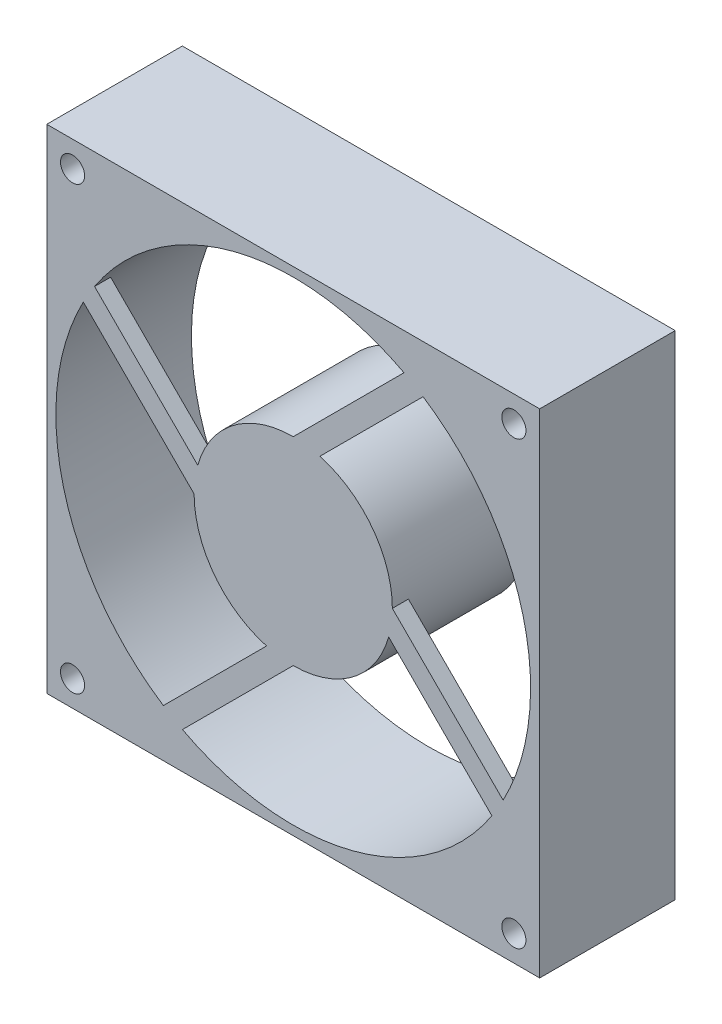
SolidWorks part; units mm, degrees
ref_plane "Front Plane" through (0, 0, 0) normal (0, 0, 1) x (1, 0, 0)
ref_plane "Top Plane" through (0, 0, 0) normal (0, 1, 0) x (1, 0, 0)
ref_plane "Right Plane" through (0, 0, 0) normal (1, 0, 0) x (0, 0, -1)
sketch "Sketch1" plane through (0, 0, 0) normal (0, 0, 1) x (1, 0, 0)
  line L1 (-46, -46) -> (46, -46)
  line L2 (-46, -46) -> (-46, 46)
  line L3 (-46, 46) -> (46, 46)
  line L4 (46, -46) -> (46, 46)
  line L5 (-46, -46) -> (46, 46) construction
  line L6 (-46, 46) -> (46, -46) construction
  line L7 (-41.189, -41.189) -> (41.189, -41.189) construction
  line L8 (-41.189, -41.189) -> (-41.189, 41.189) construction
  line L9 (-41.189, 41.189) -> (41.189, 41.189) construction
  line L10 (41.189, -41.189) -> (41.189, 41.189) construction
  line L11 (-41.189, -41.189) -> (41.189, 41.189) construction
  line L12 (-41.189, 41.189) -> (41.189, -41.189) construction
  circle A0 centre (-41.189, 41.189) radius 2.25
  circle A1 centre (41.189, 41.189) radius 2.25
  circle A2 centre (41.189, -41.189) radius 2.25
  circle A3 centre (-41.189, -41.189) radius 2.25
  circle A4 centre (0, 0) radius 44.3
  circle A5 centre (0, 0) radius 18.5
  point P0 (0, 0)
  point P6 (0, 0)
  point P15 (-39.598, 39.598)
  point P16 (39.598, -39.598)
  point P19 (0, 44.3)
  dimension "D2" = 4.5
  dimension "D5" = 37
  dimension "D1" = 92
  dimension "D3" = 112
  dimension "D4" = 1.7
extrude "Boss-Extrude1" add sketch "Sketch1" along normal mid plane 25.3 contours L1 L4 L3 L2 A4 A3 A2 A1 A0 | A5
sketch "Sketch2" plane through (0, 0, 12.65) normal (0, 0, 1) x (1, 0, 0)
  line L0 (0, 18.5) -> (20.678, 39.178)
  line L1 (4.9753, 17.8184) -> (24.238, 37.0811)
  line L2 (0, -24.5293) -> (0, 31.2045) construction
  circle A0 centre (0, 0) radius 18.5 construction
  circle A1 centre (0, 0) radius 44.3 construction
  arc A3 (20.678, 39.178) -> (24.238, 37.0811) centre (0, 0) cw
  arc A4 (0, 18.5) -> (4.9753, 17.8184) centre (0, 0) cw
  dimension "D1" = 4
  dimension "D2" = 45
extrude "Boss-Extrude2" add sketch "Sketch2" against normal blind 3
pattern_circular "CirPattern1" count 4 over 360 about axis through (0, 0, 0) along (0, 0, 1) of "Boss-Extrude2"
